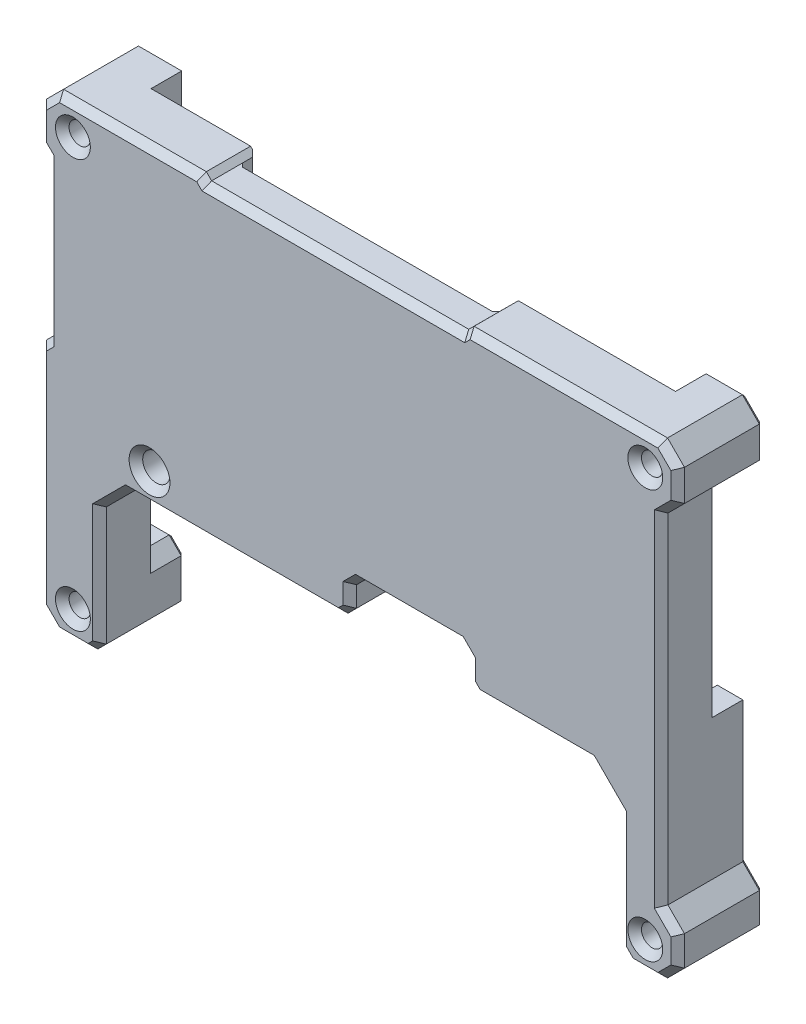
SolidWorks part; units mm, degrees
ref_plane "前视基准面" through (0, 0, 0) normal (0, 0, 1) x (1, 0, 0)
ref_plane "上视基准面" through (0, 0, 0) normal (0, 1, 0) x (1, 0, 0)
ref_plane "右视基准面" through (0, 0, 0) normal (1, 0, 0) x (0, 0, -1)
other "Configuration Table"
sketch "草图1" plane through (0, 0, 0) normal (0, 0, 1) x (1, 0, 0)
  line L1 (0, 0) -> (85, 0)
  line L2 (0, 0) -> (0, 65)
  line L3 (0, 65) -> (85, 65)
  line L4 (85, 0) -> (85, 65)
  dimension "D1" = 65
  dimension "D2" = 85
extrude "凸台-拉伸1" add sketch "草图1" along normal blind 10
sketch "草图2" plane through (0, 0, 0) normal (0, 0, -1) x (-1, 0, 0)
  circle A0 centre (-76.1669, 56.4425) radius 1.25
  circle A1 centre (-8.8888, 56.4425) radius 1.25
  circle A2 centre (-76.1669, 8.4151) radius 1.25
  circle A3 centre (-8.8888, 8.4151) radius 1.25
  dimension "D1" = 2.5
  dimension "D2" = 2.5
  dimension "D3" = 2.5
  dimension "D4" = 2.5
extrude "切除-拉伸1" cut sketch "草图2" against normal up to next
sketch "草图3" plane through (0, 0, 0) normal (0, 0, -1) x (-1, 0, 0)
  line L28 (-85, 0) -> (-85, 65) construction
  line L29 (-85, 65) -> (0, 65)
  line L30 (-85, 65) -> (-85, 0)
  line L31 (-85, 0) -> (0, 0)
  line L32 (0, 65) -> (0, 0)
  line L56 (-5, 33.4629) -> (-5.8713, 34.3342)
  line L57 (-5, 6.9926) -> (-5, 33.4629)
  line L58 (-6.9926, 5) -> (-5, 6.9926)
  line L59 (-16.2697, 5) -> (-6.9926, 5)
  line L60 (-17.4616, 6.1866) -> (-16.2697, 5)
  line L61 (-31.7436, 6.1829) -> (-17.4616, 6.1866)
  line L62 (-32.9265, 5) -> (-31.7436, 6.1829)
  line L63 (-58.7727, 5) -> (-32.9265, 5)
  line L64 (-60.0435, 6.2655) -> (-58.7727, 5)
  line L65 (-73.1524, 6.2618) -> (-60.0435, 6.2655)
  line L66 (-74.4142, 5) -> (-73.1524, 6.2618)
  line L67 (-77.9822, 5) -> (-74.4142, 5)
  line L68 (-79.9747, 6.9926) -> (-77.9822, 5)
  line L69 (-79.9747, 10.5083) -> (-79.9747, 6.9926)
  line L70 (-78.0283, 12.46) -> (-79.9747, 10.5083)
  line L71 (-78.032, 52.3531) -> (-78.0283, 12.46)
  line L72 (-79.9747, 54.2958) -> (-78.032, 52.3531)
  line L73 (-79.9747, 57.9821) -> (-79.9747, 54.2958)
  line L74 (-77.9822, 59.9747) -> (-79.9747, 57.9821)
  line L75 (-55.2451, 59.9747) -> (-77.9822, 59.9747)
  line L76 (-54.6148, 59.3497) -> (-55.2451, 59.9747)
  line L77 (-24.3949, 59.3534) -> (-54.6148, 59.3497)
  line L78 (-23.7736, 59.9747) -> (-24.3949, 59.3534)
  line L79 (-6.9926, 59.9747) -> (-23.7736, 59.9747)
  line L80 (-5, 57.9821) -> (-6.9926, 59.9747)
  line L81 (-5, 54.0174) -> (-5, 57.9821)
  line L82 (-5.875, 53.1371) -> (-5, 54.0174)
  line L83 (-5.8713, 34.3342) -> (-5.875, 53.1371)
extrude "切除-拉伸2" cut sketch "草图3" against normal up to next
sketch "草图4" plane through (0, 0, 0) normal (0, 0, -1) x (-1, 0, 0)
  line L0 (-73.1524, 6.2618) -> (-73.1524, 20.0323)
  line L1 (-73.1524, 20.0323) -> (-69.8316, 23.3532)
  line L2 (-69.8316, 23.3532) -> (-46.788, 23.3532)
  line L3 (-46.788, 23.3532) -> (-15.4038, 23.3532)
  line L4 (-15.4038, 23.3532) -> (-12.014, 19.9634)
  line L5 (-12.014, 19.9634) -> (-12.014, 6.188)
  line L6 (-31.7436, 6.1829) -> (-17.4616, 6.1866) construction
  line L7 (-12.014, 6.188) -> (-12.014, 0.194)
  line L8 (-12.014, 0.194) -> (-73.1524, 0.194)
  line L9 (-73.1524, 0.194) -> (-73.1524, 6.2618)
  line L10 (-73.1524, 6.2618) -> (-60.0435, 6.2655) construction
  dimension "D1" = 135
  dimension "D2" = 135
  dimension "D3" = 4.7938
extrude "切除-拉伸4" cut sketch "草图4" against normal up to next
sketch "草图5" plane through (0, 0, 0) normal (0, 0, -1) x (-1, 0, 0)
  line L0 (-24.3949, 59.3534) -> (-24.3949, 53.9064)
  line L1 (-24.3949, 53.9064) -> (-25.5261, 52.7749)
  line L2 (-25.5261, 52.7749) -> (-53.4826, 52.7749)
  line L3 (-53.4826, 52.7749) -> (-54.6142, 53.9061)
  line L4 (-54.6142, 53.9061) -> (-54.6148, 59.3497)
  line L5 (-24.3949, 59.3534) -> (-54.6148, 59.3497) construction
  line L6 (-23.7736, 59.9747) -> (-24.3949, 59.3534) construction
  line L7 (-24.3949, 59.3534) -> (-54.6148, 59.3497)
  dimension "D1" = 135
  dimension "D2" = 134.993
  dimension "D3" = 1.6
  dimension "D4" = 1.6
extrude "切除-拉伸7" cut sketch "草图5" against normal blind 6
sketch "草图6" plane through (0, 0, 0) normal (0, 0, -1) x (-1, 0, 0)
  line L0 (-5.8713, 34.3342) -> (-11.6713, 34.3342)
  line L1 (-5, 33.4629) -> (-5.8713, 34.3342) construction
  line L6 (-5.8713, 34.3342) -> (-5.875, 53.1371) construction
  line L7 (-5.8735, 45.2504) -> (-5.8745, 50.3342)
  line L8 (-5.8735, 45.2504) -> (-5.8713, 34.3342)
  line L9 (-5.8745, 50.3342) -> (-11.6713, 50.3342)
  line L10 (-11.6713, 50.3342) -> (-11.6713, 34.3342)
  dimension "D1" = 5.8
  dimension "D2" = 16
extrude "切除-拉伸8" cut sketch "草图6" against normal blind 6
sketch "草图7" plane through (0, 0, 0) normal (0, 0, -1) x (-1, 0, 0)
  line L0 (-76.4321, 51.2623) -> (-74.4321, 51.2623)
  line L1 (-74.4321, 51.2623) -> (-71.3195, 54.3749)
  line L2 (-71.3195, 54.3749) -> (-71.3195, 58.3749)
  line L3 (-71.3195, 58.3749) -> (-71.3195, 59.9747)
  line L4 (-76.4321, 51.2623) -> (-78.0319, 51.2623)
  line L5 (-78.0298, 28.9377) -> (-75.0298, 28.9377)
  line L6 (-75.0298, 28.9377) -> (-75.0298, 13.9377)
  line L7 (-72.9158, 11.8236) -> (-75.0298, 13.9377)
  line L8 (-24.3949, 57.6633) -> (-23.7321, 57.6633)
  line L9 (-23.7321, 57.6633) -> (-23.0617, 58.334)
  line L10 (-23.0617, 58.334) -> (-12.072, 58.334)
  line L11 (-12.072, 58.334) -> (-12.072, 55.334)
  line L12 (-12.072, 55.334) -> (-9.875, 53.1371)
  line L13 (-9.875, 53.1371) -> (-5.875, 53.1371)
  line L14 (-6.5998, 12.014) -> (-10.5998, 12.014)
  line L15 (-10.5998, 12.014) -> (-12.014, 10.5998)
  line L16 (-12.014, 10.5998) -> (-12.014, 5)
  line L17 (-6.5998, 12.014) -> (-5, 12.014)
  line L18 (-72.9158, 11.8236) -> (-73.1524, 12.0603)
  line L37 (-5.8713, 34.3342) -> (-11.6713, 34.3342)
  line L38 (-11.6713, 34.3342) -> (-11.6713, 50.3342)
  line L39 (-11.6713, 34.3342) -> (-11.6713, 50.3342)
  line L40 (-11.6713, 50.3342) -> (-5.8745, 50.3342)
  line L41 (-11.6713, 50.3342) -> (-5.8745, 50.3342)
  line L42 (-5.8745, 50.3342) -> (-5.875, 53.1371)
  line L43 (-5.875, 53.1371) -> (-5, 54.0174)
  line L44 (-5, 54.0174) -> (-5, 57.9821)
  line L45 (-5, 57.9821) -> (-6.9926, 59.9747)
  line L46 (-6.9926, 59.9747) -> (-23.7736, 59.9747)
  line L47 (-23.7736, 59.9747) -> (-24.3949, 59.3534)
  line L48 (-24.3949, 59.3534) -> (-24.3949, 53.9064)
  line L49 (-24.3949, 53.9064) -> (-25.5261, 52.7749)
  line L50 (-25.5261, 52.7749) -> (-53.4826, 52.7749)
  line L51 (-53.4826, 52.7749) -> (-54.6142, 53.9061)
  line L52 (-54.6142, 53.9061) -> (-54.6148, 59.3497)
  line L53 (-54.6148, 59.3497) -> (-55.2451, 59.9747)
  line L54 (-55.2451, 59.9747) -> (-77.9822, 59.9747)
  line L55 (-77.9822, 59.9747) -> (-79.9747, 57.9821)
  line L56 (-79.9747, 57.9821) -> (-79.9747, 54.2958)
  line L57 (-79.9747, 54.2958) -> (-78.032, 52.3531)
  line L58 (-78.032, 52.3531) -> (-78.0283, 12.46)
  line L59 (-78.0283, 12.46) -> (-79.9747, 10.5083)
  line L60 (-79.9747, 10.5083) -> (-79.9747, 6.9926)
  line L61 (-79.9747, 6.9926) -> (-77.9822, 5)
  line L62 (-77.9822, 5) -> (-74.4142, 5)
  line L63 (-74.4142, 5) -> (-73.1524, 6.2618)
  line L64 (-73.1524, 6.2618) -> (-73.1524, 20.0323)
  line L65 (-73.1524, 20.0323) -> (-69.8316, 23.3532)
  line L66 (-69.8316, 23.3532) -> (-15.4038, 23.3532)
  line L67 (-15.4038, 23.3532) -> (-12.014, 19.9634)
  line L68 (-12.014, 19.9634) -> (-12.014, 5)
  line L70 (-12.014, 5) -> (-6.9926, 5)
  line L71 (-6.9926, 5) -> (-5, 6.9926)
  line L72 (-5, 6.9926) -> (-5, 33.4629)
  line L73 (-5, 33.4629) -> (-5.8713, 34.3342)
  line L74 (-5.8713, 34.3342) -> (-11.6713, 34.3342)
  line L79 (-5.8745, 50.3342) -> (-5.875, 53.1371)
  line L80 (-5.875, 53.1371) -> (-5, 54.0174)
  line L81 (-5, 54.0174) -> (-5, 57.9821)
  line L82 (-5, 57.9821) -> (-6.9926, 59.9747)
  line L83 (-6.9926, 59.9747) -> (-23.7736, 59.9747)
  line L84 (-23.7736, 59.9747) -> (-24.3949, 59.3534)
  line L85 (-24.3949, 59.3534) -> (-24.3949, 53.9064)
  line L86 (-24.3949, 53.9064) -> (-25.5261, 52.7749)
  line L87 (-25.5261, 52.7749) -> (-53.4826, 52.7749)
  line L88 (-53.4826, 52.7749) -> (-54.6142, 53.9061)
  line L89 (-54.6142, 53.9061) -> (-54.6148, 59.3497)
  line L90 (-54.6148, 59.3497) -> (-55.2451, 59.9747)
  line L91 (-55.2451, 59.9747) -> (-77.9822, 59.9747)
  line L92 (-77.9822, 59.9747) -> (-79.9747, 57.9821)
  line L93 (-79.9747, 57.9821) -> (-79.9747, 54.2958)
  line L94 (-79.9747, 54.2958) -> (-78.032, 52.3531)
  line L95 (-78.032, 52.3531) -> (-78.0283, 12.46)
  line L96 (-78.0283, 12.46) -> (-79.9747, 10.5083)
  line L97 (-79.9747, 10.5083) -> (-79.9747, 6.9926)
  line L98 (-79.9747, 6.9926) -> (-77.9822, 5)
  line L99 (-77.9822, 5) -> (-74.4142, 5)
  line L100 (-74.4142, 5) -> (-73.1524, 6.2618)
  line L101 (-73.1524, 6.2618) -> (-73.1524, 20.0323)
  line L102 (-73.1524, 20.0323) -> (-69.8316, 23.3532)
  line L103 (-69.8316, 23.3532) -> (-15.4038, 23.3532)
  line L104 (-15.4038, 23.3532) -> (-12.014, 19.9634)
  line L105 (-12.014, 19.9634) -> (-12.014, 5)
  line L107 (-12.014, 5) -> (-6.9926, 5)
  line L108 (-6.9926, 5) -> (-5, 6.9926)
  line L109 (-5, 6.9926) -> (-5, 33.4629)
  line L110 (-5, 33.4629) -> (-5.8713, 34.3342)
  dimension "D2" = 90
  dimension "D3" = 15
  dimension "D4" = 135
  dimension "D5" = 4
  dimension "D6" = 3
  dimension "D7" = 135
  dimension "D8" = 45
  dimension "D9" = 3
  dimension "D1" = 0
extrude "切除-拉伸11" cut sketch "草图7" against normal blind 4
sketch "草图8" plane through (0, 0, 4) normal (0, 0, -1) x (-1, 0, 0)
  line L1 (-73.3481, 45.9587) -> (-65.3481, 45.9587)
  line L2 (-73.3481, 45.9587) -> (-73.3481, 40.9587)
  line L3 (-73.3481, 40.9587) -> (-65.3481, 40.9587)
  line L4 (-65.3481, 45.9587) -> (-65.3481, 40.9587)
  dimension "D1" = 5
  dimension "D2" = 8
extrude "切除-拉伸12" cut sketch "草图8" against normal blind 1
sketch "草图10" plane through (0, 0, 4) normal (0, 0, -1) x (-1, 0, 0)
  line L0 (-41.5465, 34.8898) -> (-37.5465, 34.8898)
  line L1 (-46.9465, 34.8898) -> (-41.5465, 34.8898)
  line L2 (-46.9465, 34.8898) -> (-46.9465, 28.8898)
  line L3 (-46.9465, 28.8898) -> (-41.5465, 28.8898)
  line L4 (-41.5465, 34.8898) -> (-41.5465, 28.8898)
  line L5 (-37.5465, 34.8898) -> (-32.1465, 34.8898)
  line L6 (-37.5465, 34.8898) -> (-37.5465, 28.8898)
  line L7 (-37.5465, 28.8898) -> (-32.1465, 28.8898)
  line L8 (-32.1465, 34.8898) -> (-32.1465, 28.8898)
  line L9 (-37.5465, 28.8898) -> (-41.5465, 28.8898)
  dimension "D1" = 5.4
  dimension "D2" = 6
  dimension "D3" = 5.4
  dimension "D4" = 4
extrude "凸台-拉伸2" add sketch "草图10" along normal offset from surface (2.04 mm away) 3 contours L4 L1 L2 L3 | L9 L6 L0 L4 | L8 L5 L6 L7
sketch "草图11" plane through (0, 0, 4) normal (0, 0, -1) x (-1, 0, 0)
  line L1 (-40.8318, 43.6929) -> (-36.6318, 43.6929)
  line L2 (-40.8318, 43.6929) -> (-40.8318, 38.6929)
  line L3 (-40.8318, 38.6929) -> (-36.6318, 38.6929)
  line L4 (-36.6318, 43.6929) -> (-36.6318, 38.6929)
  dimension "D1" = 4.2
  dimension "D2" = 5
extrude "凸台-拉伸3" add sketch "草图11" along normal offset from surface (1.3001 mm away) 3
sketch "草图12" plane through (0, 0, 4) normal (0, 0, -1) x (-1, 0, 0)
  line L0 (-24.6106, 30.6859) -> (-32.1465, 34.8898)
  line L1 (-30.6106, 30.6859) -> (-18.6106, 30.6859)
  line L2 (-30.6106, 30.6859) -> (-30.6106, 24.6859)
  line L3 (-30.6106, 24.6859) -> (-18.6106, 24.6859)
  line L4 (-18.6106, 30.6859) -> (-18.6106, 24.6859)
  line L5 (-32.1465, 34.8898) -> (-46.9465, 34.8898) construction
  line L6 (-32.1465, 28.8898) -> (-32.1465, 34.8898) construction
  line L7 (-32.1465, 34.8898) -> (-32.1465, 28.8898)
  line L8 (-32.1465, 28.8898) -> (-30.6106, 27.6859)
  line M47 (-32.1465, 34.8898) -> (-32.1465, 28.8898)
  dimension "D1" = 12
  dimension "D2" = 6
extrude "凸台-拉伸4" add sketch "草图12" along normal offset from surface (1.89 mm away) 3 contours L4 L1 L2 L3 | L8 L2 L1 L0 M47
sketch "草图13" plane through (0, 0, 4) normal (0, 0, -1) x (-1, 0, 0)
  line L1 (-62.8902, 40.6188) -> (-59.7758, 40.6188)
  line L2 (-62.8902, 40.6188) -> (-62.8902, 35.6362)
  line L3 (-62.8902, 35.6362) -> (-59.7758, 35.6362)
  line L4 (-59.7758, 40.6188) -> (-59.7758, 35.6362)
extrude "凸台-拉伸5" add sketch "草图13" along normal offset from surface (4 mm away) 2
sketch "草图15" plane through (0, 0, 10) normal (0, 0, 1) x (1, 0, 0)
  line L0 (69.8316, 23.3532) -> (15.4038, 23.3532) construction
  line L1 (41.4288, 23.3532) -> (55.4288, 23.3532)
  line L2 (41.4288, 23.3532) -> (41.4288, 27.7532)
  line L3 (41.4288, 27.7532) -> (55.4288, 27.7532)
  line L4 (55.4288, 23.3532) -> (55.4288, 27.7532)
  dimension "D1" = 14
  dimension "D2" = 4.4
extrude "切除-拉伸13" cut sketch "草图15" against normal up to surface (6 mm away) up to face at (69.3481, 43.4587, 4)
chamfer "倒角1" distance 1 angle 45 5 edges at (12.014, 5, 5) (55.4288, 23.3532, 7) (55.4288, 27.7532, 7) (41.4288, 27.7532, 7) (41.4288, 23.3532, 7)
chamfer "倒角2" distance 0.6 angle 45 4 edges at (59.7758, 38.1275, 4) (61.333, 40.6188, 4) (62.8902, 38.1275, 4) (61.333, 35.6362, 4)
chamfer "倒角5" distance 0.6 angle 45 4 edges at (36.6318, 41.1929, 4) (38.7318, 38.6929, 4) (40.8318, 41.1929, 4) (38.7318, 43.6929, 4)
sketch "草图16" plane through (0, 0, 4) normal (0, 0, -1) x (-1, 0, 0)
  circle A0 centre (-17.8941, 26.9463) radius 1.6
  dimension "D1" = 3.2
extrude "切除-拉伸14" cut sketch "草图16" against normal through all both and the other way through all
sketch "草图17" plane through (0, 0, 0) normal (0, 0, -1) x (-1, 0, 0)
  line L0 (-12.072, 58.334) -> (-12.072, 59.9747)
  line L2 (-6.9926, 59.9747) -> (-23.7736, 59.9747) construction
  line L15 (-24.3949, 59.3534) -> (-24.3949, 57.6633)
  line L16 (-24.3949, 57.6633) -> (-23.7321, 57.6633)
  line L17 (-23.7321, 57.6633) -> (-23.0617, 58.334)
  line L18 (-23.0617, 58.334) -> (-12.072, 58.334)
  line L19 (-12.072, 58.334) -> (-12.072, 55.334)
  line L20 (-12.072, 55.334) -> (-9.875, 53.1371)
  line L21 (-9.875, 53.1371) -> (-5.875, 53.1371)
  line L22 (-5.875, 53.1371) -> (-5, 54.0174)
  line L23 (-5, 54.0174) -> (-5, 57.9821)
  line L24 (-5, 57.9821) -> (-6.9926, 59.9747)
  line L25 (-6.9926, 59.9747) -> (-23.7736, 59.9747)
  line L26 (-23.7736, 59.9747) -> (-24.3949, 59.3534)
  line L27 (-24.3949, 59.3534) -> (-24.3949, 57.6633)
  line L28 (-24.3949, 57.6633) -> (-23.7321, 57.6633)
  line L29 (-23.7321, 57.6633) -> (-23.0617, 58.334)
  line L30 (-23.0617, 58.334) -> (-12.072, 58.334)
  line L31 (-12.072, 58.334) -> (-12.072, 55.334)
  line L32 (-12.072, 55.334) -> (-9.875, 53.1371)
  line L33 (-9.875, 53.1371) -> (-5.875, 53.1371)
  line L34 (-5.875, 53.1371) -> (-5, 54.0174)
  line L35 (-5, 54.0174) -> (-5, 57.9821)
  line L36 (-5, 57.9821) -> (-6.9926, 59.9747)
  line L37 (-6.9926, 59.9747) -> (-23.7736, 59.9747)
  line L38 (-23.7736, 59.9747) -> (-24.3949, 59.3534)
  line M15 (-24.3949, 59.3534) -> (-24.3949, 57.6633)
  line M16 (-24.3949, 57.6633) -> (-23.7321, 57.6633)
  line M17 (-23.7321, 57.6633) -> (-23.0617, 58.334)
  line M18 (-23.0617, 58.334) -> (-12.072, 58.334)
  line M25 (-6.9926, 59.9747) -> (-23.7736, 59.9747)
  line M26 (-23.7736, 59.9747) -> (-24.3949, 59.3534)
  dimension "D1" = 0
extrude "切除-拉伸15" cut sketch "草图17" against normal up to surface (4 mm away) contours L0 M18 M25 M26 M15 M16 M17 up to face at (28.7404, 29.0801, 4)
sketch "草图18" plane through (0, 0, 0) normal (0, 0, -1) x (-1, 0, 0)
  line L0 (-73.7195, 59.9747) -> (-73.7195, 54.0502)
  line L1 (-71.3195, 59.9747) -> (-77.9822, 59.9747) construction
  line L2 (-73.7195, 54.0502) -> (-75.4166, 52.3531)
  line L3 (-75.4166, 52.3531) -> (-78.032, 52.3531)
  line L12 (-78.032, 52.3531) -> (-78.0319, 51.2623)
  line L13 (-78.0319, 51.2623) -> (-74.4321, 51.2623)
  line L14 (-74.4321, 51.2623) -> (-71.3195, 54.3749)
  line L15 (-71.3195, 54.3749) -> (-71.3195, 59.9747)
  line L16 (-71.3195, 59.9747) -> (-77.9822, 59.9747)
  line L17 (-77.9822, 59.9747) -> (-79.9747, 57.9821)
  line L18 (-79.9747, 57.9821) -> (-79.9747, 54.2958)
  line L19 (-79.9747, 54.2958) -> (-78.032, 52.3531)
  line L20 (-78.032, 52.3531) -> (-78.0319, 51.2623)
  line L21 (-78.0319, 51.2623) -> (-74.4321, 51.2623)
  line L22 (-74.4321, 51.2623) -> (-71.3195, 54.3749)
  line L23 (-71.3195, 54.3749) -> (-71.3195, 59.9747)
  line L24 (-71.3195, 59.9747) -> (-77.9822, 59.9747)
  line L25 (-77.9822, 59.9747) -> (-79.9747, 57.9821)
  line L26 (-79.9747, 57.9821) -> (-79.9747, 54.2958)
  line L27 (-79.9747, 54.2958) -> (-78.032, 52.3531)
  point P8 (-78.032, 52.2837)
  line M13 (-78.032, 52.3531) -> (-78.0319, 51.2623)
  line M14 (-78.0319, 51.2623) -> (-74.4321, 51.2623)
  line M15 (-74.4321, 51.2623) -> (-71.3195, 54.3749)
  line M16 (-71.3195, 54.3749) -> (-71.3195, 59.9747)
  line M17 (-71.3195, 59.9747) -> (-77.9822, 59.9747)
  dimension "D1" = 0
  dimension "D2" = 2.4
  dimension "D3" = 2.4
extrude "切除-拉伸16" cut sketch "草图18" against normal up to surface (4 mm away) contours L2 L3 L0 M13 M14 M15 M16 M17 up to face at (28.7404, 29.0801, 4)
chamfer "倒角6" distance 0.8 angle 45 40 edges at (5.9963, 5.9963, 10) (5, 20.2277, 10) (5.4357, 33.8986, 10) (5.8732, 43.7356, 10) (5.4375, 53.5772, 10) (5, 55.9998, 10) (5.9963, 58.9784, 10) (15.3831, 59.9747, 10) (24.0842, 59.6641, 10) (39.5048, 59.3515, 10) (54.93, 59.6622, 10) (66.6136, 59.9747, 10) (78.9785, 58.9784, 10) (79.9747, 56.139, 10) (79.0034, 53.3245, 10) (78.0302, 32.4066, 10) (79.0015, 11.4841, 10) (79.9747, 8.7504, 10) (78.9785, 5.9963, 10) (76.1982, 5, 10) (73.7833, 5.6309, 10) (73.1524, 13.1471, 10) (71.492, 21.6927, 10) (27.9163, 23.3532, 10) (55.9288, 23.8532, 10) (55.4288, 25.5532, 10) (54.9288, 27.2532, 10) (48.4288, 27.7532, 10) (41.9288, 27.2532, 10) (41.4288, 25.5532, 10) (40.9288, 23.8532, 10) (13.7089, 21.6583, 10) (12.014, 12.9817, 10) (11.514, 5.5, 10) (9.0033, 5, 10) (7.6388, 56.4425, 10) (74.9169, 8.4151, 10) (7.6388, 8.4151, 10) (74.9169, 56.4425, 10) (16.2941, 26.9463, 10)
chamfer "倒角7" distance 0.4 angle 45 43 edges at (59.7758, 38.1275, 0) (61.333, 35.6362, 0) (62.8902, 38.1275, 0) (61.333, 40.6188, 0) (40.8318, 41.1929, 2.6999) (38.7318, 43.6929, 2.6999) (36.6318, 41.1929, 2.6999) (38.7318, 38.6929, 2.6999) (74.9169, 56.4425, 0) (74.568, 53.2016, 0) (76.7243, 52.3531, 0) (79.0034, 53.3245, 0) (79.9747, 56.139, 0) (78.9785, 58.9784, 0) (75.8509, 59.9747, 0) (73.7195, 57.0124, 0) (73.7833, 5.6309, 0) (76.1982, 5, 0) (78.9785, 5.9963, 0) (79.9747, 8.7504, 0) (79.0015, 11.4841, 0) (78.0291, 20.6989, 0) (76.5298, 28.9377, 0) (75.0298, 21.4377, 0) (74.0911, 12.999, 0) (73.1524, 9.1611, 0) (74.9169, 8.4151, 0) (11.3069, 11.3069, 0) (7.7999, 12.014, 0) (5, 9.5033, 0) (5.9963, 5.9963, 0) (9.0033, 5, 0) (11.514, 5.5, 0) (12.014, 8.2999, 0) (7.6388, 8.4151, 0) (7.6388, 56.4425, 0) (5.9963, 58.9784, 0) (5, 55.9998, 0) (5.4375, 53.5772, 0) (7.875, 53.1371, 0) (10.9735, 54.2355, 0) (12.072, 57.6543, 0) (9.5323, 59.9747, 0)
chamfer "倒角8" distance 0.4 angle 45 8 edges at (8.7729, 50.3342, 6) (11.6713, 50.3342, 5) (11.6713, 42.3342, 6) (8.7713, 34.3342, 6) (11.6713, 34.3342, 5) (8.7729, 50.3342, 4) (11.6713, 42.3342, 4) (8.7713, 34.3342, 4)
chamfer "倒角9" distance 0.4 angle 45 10 edges at (54.6145, 56.6279, 4) (54.0484, 53.3405, 4) (24.3949, 56.6299, 4) (24.9605, 53.3407, 4) (39.5044, 52.7749, 4) (54.6145, 56.6279, 6) (54.0484, 53.3405, 6) (24.3949, 56.6299, 6) (24.9605, 53.3407, 6) (39.5044, 52.7749, 6)
chamfer "倒角11" distance 0.4 angle 45 4 edges at (69.3481, 45.9587, 5) (65.3481, 43.4587, 5) (69.3481, 40.9587, 5) (73.3481, 43.4587, 5)
